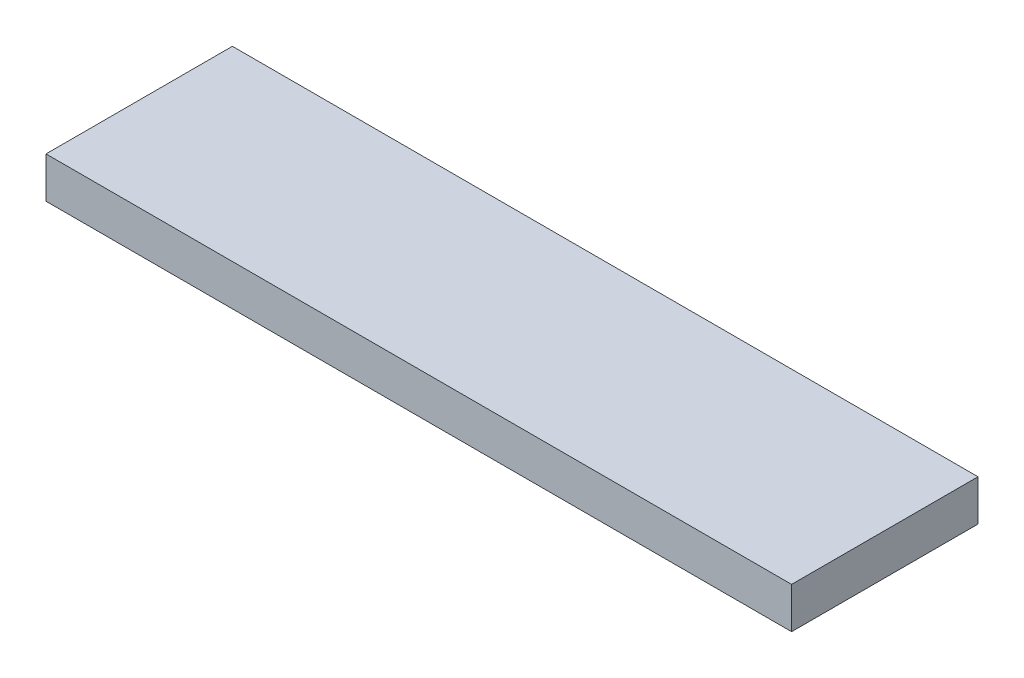
SolidWorks part; units mm, degrees
ref_plane "前视基准面" through (0, 0, 0) normal (0, 0, 1) x (1, 0, 0)
ref_plane "上视基准面" through (0, 0, 0) normal (0, 1, 0) x (1, 0, 0)
ref_plane "右视基准面" through (0, 0, 0) normal (1, 0, 0) x (0, 0, -1)
sketch "草图1" plane through (0, 0, 0) normal (0, 1, 0) x (1, 0, 0)
  line L1 (-500, -125) -> (500, -125)
  line L2 (-500, -125) -> (-500, 125)
  line L3 (-500, 125) -> (500, 125)
  line L4 (500, -125) -> (500, 125)
  line L5 (-500, -125) -> (500, 125) construction
  line L6 (-500, 125) -> (500, -125) construction
  point P0 (0, 0)
  dimension "D1" = 1000
  dimension "D2" = 250
extrude "凸台-拉伸1" add sketch "草图1" along normal blind 55
sketch "底面" plane through (0, 0, 0) normal (0, -1, 0) x (1, 0, 0)
  line L1 (-435, 65) -> (-410, 65)
  line L2 (-435, -65) -> (-410, -65)
  line L3 (-500, -125) -> (-500, 125) construction
  line L4 (435, -65) -> (410, -65)
  line L6 (435, 65) -> (410, 65)
  line L7 (-500, 125) -> (500, 125) construction
  line L8 (-410, 125) -> (-410, -125) construction
  line L10 (500, -125) -> (-500, -125) construction
  line L11 (0, 125) -> (0, -125) construction
  line L14 (-320, 125) -> (-500, 125) construction
  line L15 (-500, 125) -> (-500, 0) construction
  line L16 (-500, 0) -> (-500, -125) construction
  line L17 (-500, -125) -> (-320, -125) construction
  line L23 (-320, 125) -> (-320, -125) construction
  line L24 (320, 125) -> (320, -125) construction
  line L25 (-500, -65) -> (-500, 65) construction
  line L26 (-500, 65) -> (-320, 65) construction
  line L27 (-500, -65) -> (-320, -65) construction
  line L28 (410, 125) -> (410, -125) construction
  arc A0 (-320, 125) -> (-369.8487, 91.7676) centre (-320, 70.9973) ccw
  arc A1 (-500, 0) -> (-435, 65) centre (-435, 0) cw
  arc A2 (-500, 0) -> (-435, -65) centre (-435, 0) ccw
  arc A3 (-369.8487, 91.7676) -> (-410, 65) centre (-410, 108.4973) cw
  arc A4 (-367.5088, -93.3274) -> (-410, -65) centre (-410, -111.0321) ccw
  arc A5 (-320, -125) -> (-367.5088, -93.3274) centre (-320, -73.5321) cw
  arc A6 (320, -125) -> (367.5088, -93.3274) centre (320, -73.5321) ccw
  arc A7 (367.5088, -93.3274) -> (410, -65) centre (410, -111.0321) cw
  arc A8 (500, 0) -> (435, -65) centre (435, 0) cw
  arc A9 (500, 0) -> (435, 65) centre (435, 0) ccw
  arc A10 (369.8487, 91.7676) -> (410, 65) centre (410, 108.4973) ccw
  arc A11 (320, 125) -> (369.8487, 91.7676) centre (320, 70.9973) cw
  point P40 (-500, 0)
  dimension "D2" = 130
ref_plane "基准面4" through (-320, 0, 0) normal (-1, 0, 0) x (0, 0, 1)
ref_plane "基准面5" through (-410, 0, 0) normal (-1, 0, 0) x (0, 0, 1)
ref_plane "基准面6" [suppressed] through (320, 0, 0) normal (1, 0, 0) x (0, 0, -1)
ref_plane "基准面7" [suppressed] through (410, 0, 0) normal (1, 0, 0) x (0, 0, -1)
sketch "桥(" plane through (-320, 0, 0) normal (-1, 0, 0) x (0, 0, 1)
  line L0 (0, 0) -> (0, 30) construction
  line L1 (73.3962, 30) -> (-73.3962, 30)
  line L2 (0, 30) -> (0, 50) construction
  line L4 (-125, 55) -> (-125, 0) construction
  arc A0 (-125, 50) -> (-73.3962, 30) centre (-73.3962, 106.5738) ccw
  arc A1 (73.3962, 30) -> (125, 50) centre (73.3962, 106.5738) ccw
  point P6 (0, 30)
  point P18 (0, 50)
  dimension "D1" = 30
  dimension "D2" = 146.7924
  dimension "D3" = 20
sketch "桥{{" plane through (-410, 0, 0) normal (-1, 0, 0) x (0, 0, 1)
  line L6 (-65, 30) -> (65, 30)
  arc A0 (-125, 50) -> (-65, 30) centre (-125, -50) cw
  arc A1 (125, 50) -> (65, 30) centre (125, -50) ccw
sketch "桥)" [suppressed] plane through (320, 0, 0) normal (1, 0, 0) x (0, 0, -1)
  line L0 (-73.3962, 30) -> (73.3962, 30) construction
  line L1 (-73.3962, 30) -> (73.3962, 30)
  arc A0 (-125, 50) -> (-73.3962, 30) centre (-73.3962, 106.5738) ccw construction
  arc A1 (-125, 50) -> (-73.3962, 30) centre (-73.3962, 106.5738) ccw
  arc A2 (73.3962, 30) -> (125, 50) centre (73.3962, 106.5738) ccw construction
  arc A3 (73.3962, 30) -> (125, 50) centre (73.3962, 106.5738) ccw
sketch "桥}}" [suppressed] plane through (410, 0, 0) normal (1, 0, 0) x (0, 0, -1)
  line L0 (65, 30) -> (-65, 30) construction
  line L1 (65, 30) -> (-65, 30)
  arc A0 (125, 50) -> (65, 30) centre (125, -50) ccw construction
  arc A1 (-65, 30) -> (-125, 50) centre (-125, -50) ccw construction
  arc A2 (125, 50) -> (65, 30) centre (125, -50) ccw
  arc A3 (-65, 30) -> (-125, 50) centre (-125, -50) ccw
sketch "草图12" plane through (0, 0, 0) normal (1, 0, 0) x (0, 0, -1)
  line L0 (-73.3962, 30) -> (73.3962, 30)
  arc A0 (-73.3962, 30) -> (-125, 50) centre (-73.3962, 106.5738) cw
  arc A1 (73.3962, 30) -> (125, 50) centre (73.3962, 106.5738) ccw
sketch3d "3D草图3" [suppressed]
  line L0 (320, 50, 125) -> (410, 50, 125)
  line L1 (410, 30, 65) -> (320, 30, 73.3962)
  line L2 (410, 30, -65) -> (410, 30, 65) construction
  line L3 (410, 50, -125) -> (320, 50, -125)
  line L4 (320, 30, -73.3962) -> (410, 30, -65)
  line L5 (320, 30, 73.3962) -> (320, 30, -73.3962) construction
  arc A0 (410, 30, 65) -> (410, 50, 125) centre (410, -50, 125) ccw construction
  arc A1 (320, 50, 125) -> (320, 30, 73.3962) centre (320, 106.5738, 73.3962) ccw construction
  arc A2 (320, 30, -73.3962) -> (320, 50, -125) centre (320, 106.5738, -73.3962) ccw construction
  arc A3 (410, 50, -125) -> (410, 30, -65) centre (410, -50, -125) ccw construction
  point P21 (510, -50, 125)
  point P29 (396.5738, 106.5738, 73.3962)
  point P41 (396.5738, 106.5738, -73.3962)
  point P45 (510, -50, -125)
surface "曲面-放样3" [suppressed]
